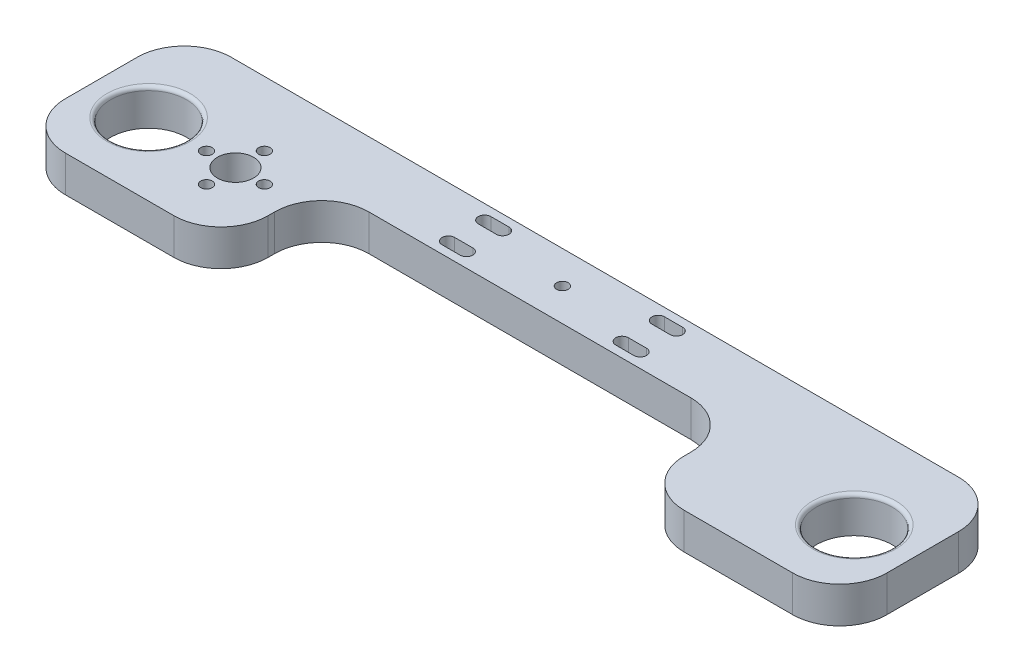
SolidWorks part; units mm, degrees
ref_plane "Front Plane" through (0, 0, 0) normal (0, 0, 1) x (1, 0, 0)
ref_plane "Top Plane" through (0, 0, 0) normal (0, 1, 0) x (1, 0, 0)
ref_plane "Right Plane" through (0, 0, 0) normal (1, 0, 0) x (0, 0, -1)
sketch "Sketch1" plane through (0, 0, 0) normal (0, 1, 0) x (1, 0, 0)
  line L4 (108.647, -20) -> (108.647, 25.8405)
  line L5 (-62.353, 7.8405) -> (52.647, 7.8405)
  line L11 (-62.353, 7.8405) -> (-62.353, -20)
  line L21 (52.647, 7.8405) -> (52.647, -20)
  line L24 (-118.353, -20) -> (-62.353, -20)
  line L25 (52.647, -20) -> (108.647, -20)
  line L28 (-118.353, -20) -> (-118.353, 25.8405)
  line L35 (-118.353, 25.8405) -> (108.647, 25.8405)
  circle A6 centre (92.647, 0) radius 10.5
  circle A12 centre (-102.353, 0) radius 10.5
  dimension "D3" = 21
  dimension "D5" = 40
  dimension "D7" = 195
  dimension "D4" = 21
  dimension "D1" = 16
  dimension "D8" = 27.8405
  dimension "D13" = 20
  dimension "D14" = 20
  dimension "D2" = 16
  dimension "D6" = 40
  dimension "D9" = 27.8405
  dimension "D10" = 56
  dimension "D11" = 56
extrude "Boss-Extrude1" add sketch "Sketch1" along normal blind 10
sketch "Sketch4" plane through (0, 10, 0) normal (0, 1, 0) x (1, 0, 0)
  line L0 (-4.853, 7.8405) -> (-4.853, 25.8405) construction
  line L1 (-118.353, 25.8405) -> (108.647, 25.8405) construction
  line L8 (-62.353, 7.8405) -> (52.647, 7.8405) construction
  circle A1 centre (-4.853, 16.8405) radius 1.6
  dimension "D1" = 0
  dimension "D2" = 9
  dimension "D5" = 3.2
fillet "Fillet1" radius 13 8 edges at (52.647, 5, -7.8405) (52.647, 5, 20) (108.647, 5, 20) (108.647, 5, -25.8405) (-118.353, 5, -25.8405) (-62.353, 5, -7.8405) (-62.353, 5, 20) (-118.353, 5, 20)
sketch "Sketch8" plane through (0, 10, 0) normal (0, 1, 0) x (1, 0, 0)
  line L0 (-49.353, 7.8405) -> (39.647, 7.8405) construction
  line L1 (-28.853, 21.8405) -> (-28.853, 11.8405) construction
  line L2 (-31.353, 21.8405) -> (-26.353, 21.8405) construction
  line L3 (-31.353, 23.5905) -> (-26.353, 23.5905)
  line L4 (-31.353, 20.0905) -> (-26.353, 20.0905)
  line L5 (-31.353, 11.8405) -> (-26.353, 11.8405) construction
  line L6 (-31.353, 13.5905) -> (-26.353, 13.5905)
  line L7 (-31.353, 10.0905) -> (-26.353, 10.0905)
  line L8 (21.647, 11.8405) -> (16.647, 11.8405) construction
  line L9 (21.647, 13.5905) -> (16.647, 13.5905)
  line L10 (21.647, 10.0905) -> (16.647, 10.0905)
  line L11 (21.647, 21.8405) -> (16.647, 21.8405) construction
  line L12 (21.647, 23.5905) -> (16.647, 23.5905)
  line L13 (21.647, 20.0905) -> (16.647, 20.0905)
  line L14 (19.147, 21.8405) -> (19.147, 11.8405) construction
  line L15 (-105.353, -20) -> (-75.353, -20) construction
  line L16 (-105.353, 25.8405) -> (95.647, 25.8405) construction
  line L17 (-62.353, -5.1595) -> (-62.353, -7) construction
  line L18 (-4.853, 7.8405) -> (-4.853, 25.8405) construction
  line L19 (-4.853, 16.8405) -> (-4.853, 25.8405) construction
  line L20 (-28.853, 16.8405) -> (19.147, 16.8405) construction
  arc A8 (21.647, 13.5905) -> (21.647, 10.0905) centre (21.647, 11.8405) cw
  circle A9 centre (-86.353, 0) radius 1.6
  circle A10 centre (-78.353, 0) radius 5
  circle A11 centre (-78.353, -8) radius 1.6
  circle A12 centre (-70.353, 0) radius 1.6
  circle A13 centre (-78.353, 8) radius 1.6
  arc A15 (-31.353, 23.5905) -> (-31.353, 20.0905) centre (-31.353, 21.8405) ccw
  arc A16 (-26.353, 20.0905) -> (-26.353, 23.5905) centre (-26.353, 21.8405) ccw
  arc A17 (-31.353, 13.5905) -> (-31.353, 10.0905) centre (-31.353, 11.8405) ccw
  arc A18 (-26.353, 10.0905) -> (-26.353, 13.5905) centre (-26.353, 11.8405) ccw
  arc A19 (16.647, 10.0905) -> (16.647, 13.5905) centre (16.647, 11.8405) cw
  arc A20 (21.647, 23.5905) -> (21.647, 20.0905) centre (21.647, 21.8405) cw
  arc A21 (16.647, 20.0905) -> (16.647, 23.5905) centre (16.647, 21.8405) cw
  point P20 (-24.603, 21.8405)
  point P35 (-28.853, 21.8405)
  point P40 (-28.853, 11.8405)
  point P53 (19.147, 11.8405)
  point P60 (19.147, 21.8405)
  dimension "D1" = 10
  dimension "D5" = 3.2
  dimension "D7" = 8
  dimension "D11" = 12
  dimension "D12" = 20
  dimension "D14" = 17.8405
  dimension "D15" = 8
  dimension "D16" = 48
  dimension "D2" = 3.2
  dimension "D3" = 3.2
  dimension "D4" = 3.2
  dimension "D6" = 8
  dimension "D8" = 8
  dimension "D9" = 8
  dimension "D10" = 20
  dimension "D13" = 20
  dimension "D20" = 1.75
  dimension "D21" = 5
  dimension "D22" = 1.75
  dimension "D24" = 1.75
  dimension "D26" = 1.75
  dimension "D35" = 43
  dimension "D36" = 43
  dimension "D17" = 10
  dimension "D18" = 10
  dimension "D19" = 5
  dimension "D23" = 5
  dimension "D25" = 5
  dimension "D27" = 9
  dimension "D28" = 9
  dimension "D29" = 2.25
  dimension "D30" = 2.25
  dimension "D31" = 2.25
  dimension "D32" = 2.25
  dimension "D33" = 19.75
  dimension "D34" = 0
extrude "Cut-Extrude5" cut sketch "Sketch8" against normal through all
extrude "Cut-Extrude6" cut sketch "Sketch4" against normal blind 10
fillet "Fillet2" radius 1 2 edges at (-102.353, 10, 10.5) (92.647, 10, 10.5)
